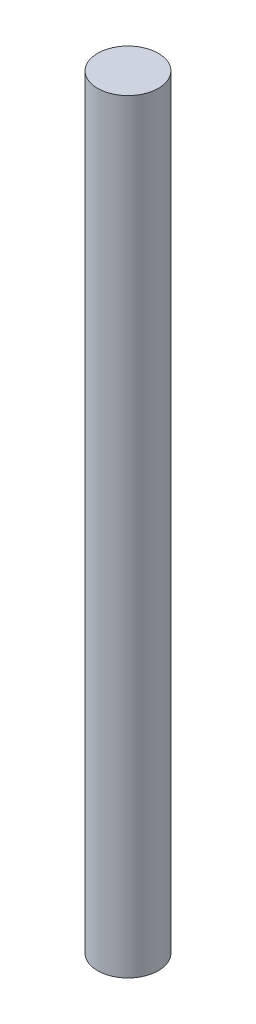
SolidWorks part; units mm, degrees
material "1.4105 (X6CrMoS17)"
ref_plane "Plano frontal" through (0, 0, 0) normal (0, 0, 1) x (1, 0, 0)
ref_plane "Plano superior" through (0, 0, 0) normal (0, 1, 0) x (1, 0, 0)
ref_plane "Plano direito" through (0, 0, 0) normal (1, 0, 0) x (0, 0, -1)
sketch "Esboço1" plane through (0, 0, 0) normal (0, 1, 0) x (1, 0, 0)
  circle A0 centre (0, 0) radius 2.385
  dimension "D1" = 4.77
extrude "Ressalto-extrusão2" add sketch "Esboço1" along normal blind 60
